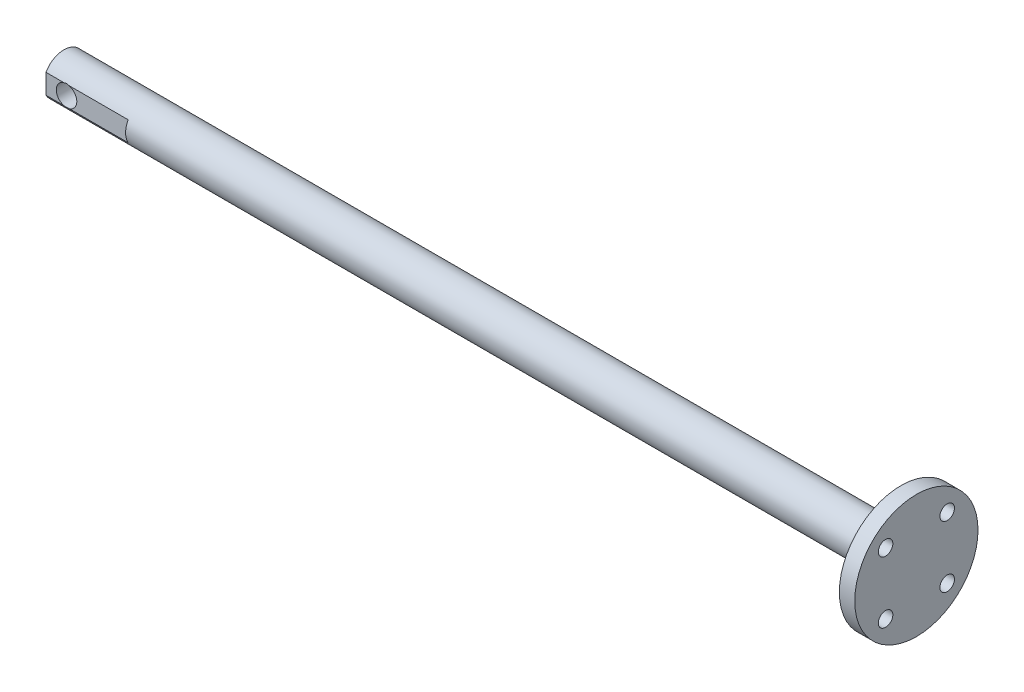
SolidWorks part; units mm, degrees
ref_plane "Front Plane" through (0, 0, 0) normal (0, 0, 1) x (1, 0, 0)
ref_plane "Top Plane" through (0, 0, 0) normal (0, 1, 0) x (1, 0, 0)
ref_plane "Right Plane" through (0, 0, 0) normal (1, 0, 0) x (0, 0, -1)
sketch "Sketch1" plane through (0, 0, 0) normal (1, 0, 0) x (0, 0, -1)
  circle A0 centre (0, 0) radius 19.05
  dimension "D1" = 38.1
extrude "Boss-Extrude1" add sketch "Sketch1" along normal blind 263.525
sketch "Sketch2" plane through (0, 0, 0) normal (0, 0, 1) x (1, 0, 0)
  line L0 (-16.5207, 0) -> (279.5841, 0) construction
  line L1 (0, 6.35) -> (258.7625, 6.35)
  line L2 (258.7625, 6.35) -> (258.7625, 19.05)
  line L3 (263.525, 19.05) -> (0, 19.05) construction
  line L4 (258.7625, 19.05) -> (0, 19.05)
  line L5 (0, 19.05) -> (0, 6.35)
  line L6 (263.525, -19.05) -> (263.525, 19.05) construction
  dimension "D1" = 6.35
  dimension "D2" = 4.7625
revolve "Cut-Revolve1" cut sketch "Sketch2" angle 360 about L0
sketch "Sketch8" plane through (0, 0, 0) normal (0, 1, 0) x (1, 0, 0)
  line L0 (-5.5022, 0) -> (24.2999, 0) construction
  line L1 (0, 6.35) -> (25.4, 6.35)
  line L2 (0, 6.35) -> (0, 5.5562)
  line L3 (0, 5.5562) -> (25.4, 5.5562)
  line L4 (25.4, 6.35) -> (25.4, 5.5562)
  line L5 (25.4, -6.35) -> (25.4, -5.5562)
  line L6 (0, -5.5562) -> (25.4, -5.5562)
  line L7 (0, -6.35) -> (0, -5.5562)
  line L8 (0, -6.35) -> (25.4, -6.35)
  dimension "D1" = 25.4
  dimension "D2" = 0.7937
extrude "Cut-Extrude1" cut sketch "Sketch8" against normal through all and the other way through all
hole_wizard "1 (1) Diameter Hole2" positions "Sketch10" profile "Sketch11" hole size "1" standard "ANSI Inch" end condition through all
sketch "Sketch10" plane through (0, 0, -5.5562) normal (0, 0, -1) x (-1, 0, 0)
  line L0 (-14.7038, 0) -> (11.7279, 0) construction
  line L2 (0, 3.0742) -> (0, -3.0742) construction
  point P0 (-6.35, 0)
  dimension "D1" = 6.35
sketch "Sketch11" plane through (6.35, 0, -5.5562) normal (1, 0, 0) x (0, 1, 0)
  line L0 (0, 0) -> (0, 24.6062)
  line L1 (0, 24.6062) -> (3.175, 24.6062)
  line L2 (3.175, 24.6062) -> (3.175, 0)
  line L5 (3.175, 0) -> (0, 0)
  line L11 (0, -6.35) -> (0, 107.95) construction
  dimension "Thru Hole Dia." = 6.35
  dimension "Thru Hole Depth" = 24.6062
hole_wizard "#16 (0.177) Diameter Hole1" positions "Sketch14" profile "Sketch13" hole size "#16" standard "ANSI Inch"
sketch "Sketch14" plane through (258.7625, 0, 0) normal (-1, 0, 0) x (0, 0, 1)
  line L1 (-9.525, -9.525) -> (9.525, -9.525) construction
  line L2 (-9.525, -9.525) -> (-9.525, 9.525) construction
  line L3 (-9.525, 9.525) -> (9.525, 9.525) construction
  line L4 (9.525, -9.525) -> (9.525, 9.525) construction
  circle A0 centre (0, 0) radius 19.05 construction
  circle A1 centre (0, 0) radius 19.05 construction
  point P2 (9.525, 9.525)
  point P85 (-9.525, -9.525)
  point P86 (-9.525, 9.525)
  point P87 (9.525, -9.525)
  dimension "D1" = 19.05
  dimension "D2" = 9.525
  dimension "D3" = 9.525
sketch "Sketch13" plane through (258.7625, 9.525, 9.525) normal (0, 1, 0) x (0, 0, 1)
  line L0 (0, 0) -> (0, 26.7507)
  line L1 (0, 26.7507) -> (2.2479, 25.4)
  line L2 (2.2479, 25.4) -> (2.2479, 0)
  line L5 (2.2479, 0) -> (0, 0)
  line L10 (0, 26.7507) -> (-2.2479, 25.4) construction
  line L11 (0, -6.35) -> (0, 107.95) construction
  dimension "Hole Dia." = 4.4958
  dimension "Hole Depth" = 25.4
  dimension "Drill Angle" = 118
